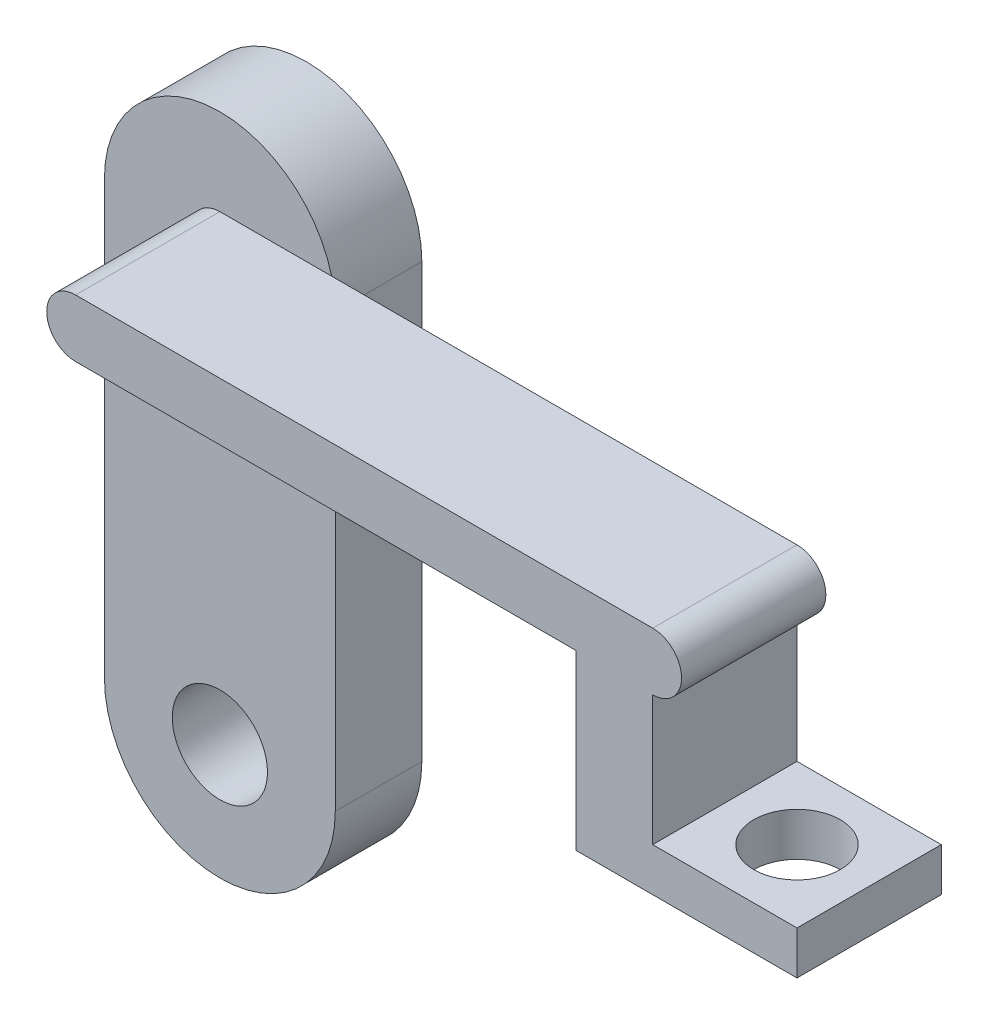
SolidWorks part; units mm, degrees
ref_plane "Front Plane" through (0, 0, 0) normal (0, 0, 1) x (1, 0, 0)
ref_plane "Top Plane" through (0, 0, 0) normal (0, 1, 0) x (1, 0, 0)
ref_plane "Right Plane" through (0, 0, 0) normal (1, 0, 0) x (0, 0, -1)
sketch "Sketch3" plane through (0, 0, 0) normal (0, 0, 1) x (1, 0, 0)
  line L0 (0, 0) -> (0, 15) construction
  line L1 (0, -55) -> (0, 55) construction
  line L2 (-4, 0) -> (-4, 15)
  line L3 (4, 0) -> (4, 15)
  arc A0 (-4, 0) -> (4, 0) centre (0, 0) ccw
  arc A1 (4, 15) -> (-4, 15) centre (0, 15) ccw
  circle A2 centre (0, 0) radius 1.65
  point P5 (0, 7.5)
  dimension "D1" = 4
  dimension "D2" = 3.3
  dimension "D3" = 15
extrude "Boss-Extrude1" add sketch "Sketch3" along normal blind 3
sketch "Sketch4" plane through (0, 0, 3) normal (0, 0, 1) x (1, 0, 0)
  line L0 (0, 15) -> (20, 15) construction
  line L1 (0, 16) -> (20, 16)
  line L2 (0, 14) -> (20, 14)
  arc A0 (0, 16) -> (0, 14) centre (0, 15) ccw
  arc A1 (20, 14) -> (20, 16) centre (20, 15) ccw
  point P3 (10, 15)
  dimension "D1" = 1
  dimension "D2" = 20
extrude "Boss-Extrude2" add sketch "Sketch4" along normal blind 5
sketch "Sketch11" plane through (0, 14, 0) normal (0, -1, 0) x (1, 0, 0)
  line L0 (20, 8) -> (20, 3) construction
  line L1 (20, 8) -> (17.3442, 8)
  line L2 (20, 8) -> (20, 3)
  line L3 (20, 3) -> (17.3442, 3)
  line L4 (17.3442, 8) -> (17.3442, 3)
  line L5 (21, 8) -> (20, 8) construction
  line L6 (4, 3) -> (20, 3) construction
extrude "Boss-Extrude6" add sketch "Sketch11" along normal blind 6
sketch "Sketch12" plane through (20, 0, 0) normal (1, 0, 0) x (0, 0, -1)
  line L0 (-3, 8) -> (-3, 14) construction
  line L1 (-8, 8) -> (-3, 8)
  line L2 (-8, 8) -> (-8, 9.5021)
  line L3 (-8, 9.5021) -> (-3, 9.5021)
  line L4 (-3, 8) -> (-3, 9.5021)
extrude "Boss-Extrude7" add sketch "Sketch12" along normal blind 5
sketch "Sketch13" plane through (0, 9.5021, 0) normal (0, 1, 0) x (1, 0, 0)
  circle A0 centre (22.5, -5.5) radius 1.5
  dimension "D1" = 3
extrude "Cut-Extrude3" cut sketch "Sketch13" against normal blind 5
